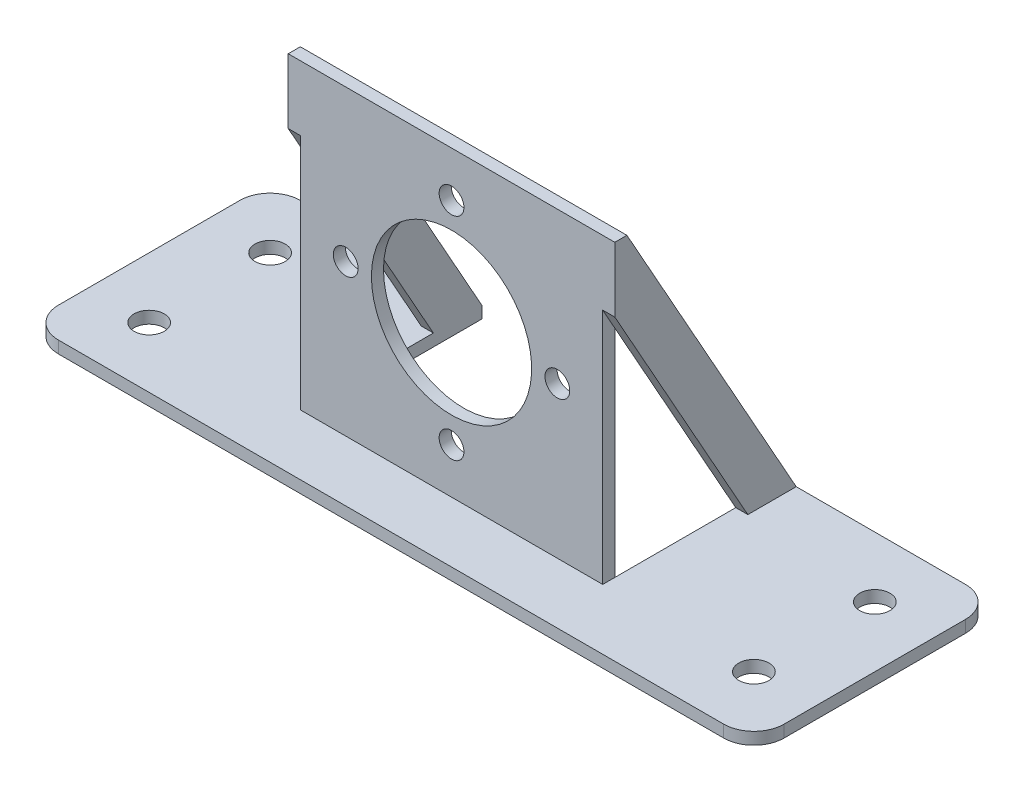
SolidWorks part; units mm, degrees
material "AISI 304"
ref_plane "前视基准面" through (0, 0, 0) normal (0, 0, 1) x (1, 0, 0)
ref_plane "上视基准面" through (0, 0, 0) normal (0, 1, 0) x (1, 0, 0)
ref_plane "右视基准面" through (0, 0, 0) normal (1, 0, 0) x (0, 0, -1)
sketch "Sketch1" plane through (0, 0, 0) normal (0, 1, 0) x (1, 0, 0)
  line L0 (35, 40) -> (35, 10)
  line L1 (0, 0) -> (120, 0)
  line L2 (0, 0) -> (0, 40)
  line L3 (0, 40) -> (35, 40)
  line L4 (120, 0) -> (120, 40)
  line L5 (35, 10) -> (85, 10)
  line L6 (85, 10) -> (85, 40)
  line L7 (85, 40) -> (120, 40)
  line L8 (10, 0) -> (10, 40) construction
  line L9 (60, 0) -> (60, 52.2367) construction
  line L10 (110, 0) -> (110, 40) construction
  circle A0 centre (10, 30) radius 2.5
  circle A1 centre (10, 10) radius 2.5
  circle A2 centre (110, 10) radius 2.5
  circle A3 centre (110, 30) radius 2.5
  dimension "D6" = 10
  dimension "D7" = 5
  dimension "D8" = 5
  dimension "D9" = 10
  dimension "D10" = 20
  dimension "D1" = 120
  dimension "D2" = 40
  dimension "D3" = 35
  dimension "D4" = 35
  dimension "D5" = 30
extrude "Boss-Extrude1" add sketch "Sketch1" along normal blind 2
sketch "Sketch2" plane through (0, 0, -10) normal (0, 0, -1) x (-1, 0, 0)
  line L0 (-60, 0) -> (-60, 52) construction
  line L1 (-85, 0) -> (-35, 0)
  line L2 (-85, 0) -> (-85, 52)
  line L3 (-85, 52) -> (-35, 52)
  line L4 (-35, 0) -> (-35, 52)
  line L5 (-85, 27) -> (-35, 27) construction
  circle A0 centre (-60, 27) radius 13.25
  circle A1 centre (-60, 27) radius 17.5 construction
  circle A2 centre (-60, 44.5) radius 2.05
  circle A3 centre (-42.5, 27) radius 2.05
  circle A4 centre (-60, 9.5) radius 2.05
  circle A5 centre (-77.5, 27) radius 2.05
  dimension "D4" = 26.5
  dimension "D5" = 35
  dimension "D6" = 4.1
  dimension "D7" = 4.1
  dimension "D8" = 4.1
  dimension "D9" = 4.1
  dimension "D1" = 50
  dimension "D2" = 52
  dimension "D3" = 27
extrude "Boss-Extrude2" add sketch "Sketch2" along normal blind 2
sketch "Sketch3" plane through (35, 0, 0) normal (-1, 0, 0) x (0, 0, 1)
  line L0 (-12, 52) -> (-40, 2)
  line L1 (-40, 2) -> (-32, 2)
  line L2 (-10, 41.2857) -> (-10, 52)
  line L3 (-10, 52) -> (-12, 52)
  line L4 (-32, 2) -> (-10, 41.2857)
  dimension "D1" = 8
extrude "Boss-Extrude3" add sketch "Sketch3" along normal blind 2
sketch "Sketch4" plane through (85, 0, 0) normal (1, 0, 0) x (0, 0, -1)
  line L0 (10, 52) -> (10, 41.2857)
  line L1 (32, 2) -> (40, 2)
  line L2 (40, 2) -> (12, 52)
  line L3 (12, 52) -> (10, 52)
  line L4 (32, 2) -> (10, 41.2857)
  dimension "D1" = 8
extrude "Boss-Extrude4" add sketch "Sketch4" along normal blind 2
fillet "Fillet1" radius 5 4 edges at (0, 1, 0) (0, 1, -40) (120, 1, 0) (120, 1, -40)
